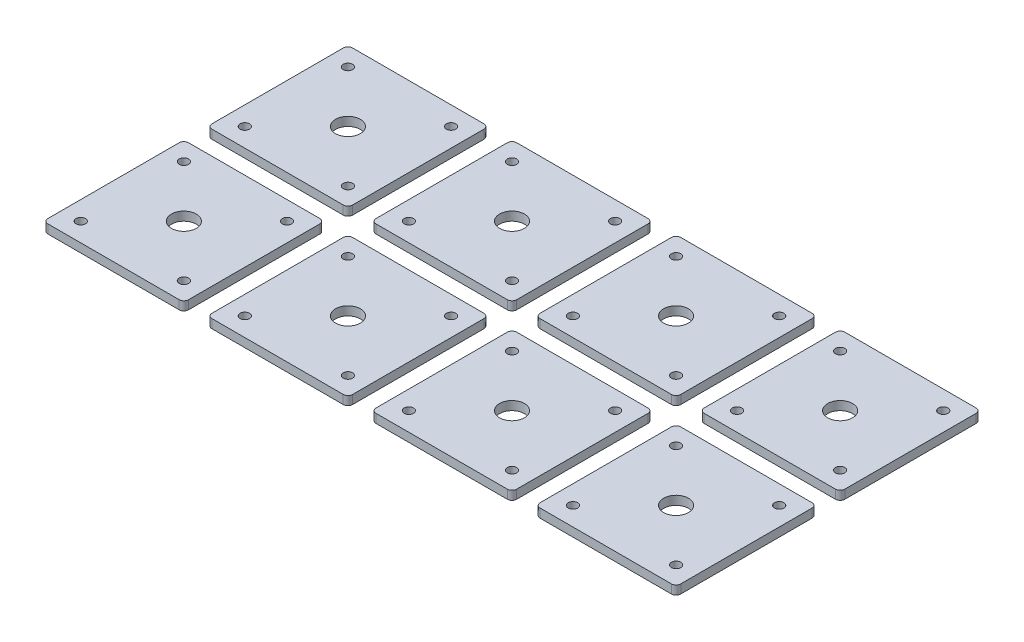
SolidWorks part; units mm, degrees
material "Acrylic (Medium-high impact)"
ref_plane "Front" through (0, 0, 0) normal (0, 0, 1) x (1, 0, 0)
ref_plane "Top" through (0, 0, 0) normal (0, 1, 0) x (1, 0, 0)
ref_plane "Right" through (0, 0, 0) normal (1, 0, 0) x (0, 0, -1)
sketch "Sketch1" plane through (0, 0, 0) normal (0, 0, 1) x (1, 0, 0)
  line L0 (-22.225, 0) -> (22.225, 0)
  dimension "D1" = 44.45
sketch "Sketch2" plane through (0, 0, 0) normal (0, 1, 0) x (1, 0, 0)
  line L0 (-13.97, 13.97) -> (13.97, 13.97) construction
  line L1 (-13.97, 13.97) -> (-13.97, -13.97) construction
  line L2 (-13.97, -13.97) -> (13.97, -13.97) construction
  line L3 (13.97, 13.97) -> (13.97, -13.97) construction
  line L4 (-13.97, 13.97) -> (13.97, -13.97) construction
  line L5 (-13.97, -13.97) -> (13.97, 13.97) construction
  line L7 (-19.05, 19.05) -> (19.05, 19.05)
  line L8 (-19.05, 19.05) -> (-19.05, -19.05)
  line L9 (-19.05, -19.05) -> (19.05, -19.05)
  line L10 (19.05, 19.05) -> (19.05, -19.05)
  line L11 (-19.05, 19.05) -> (19.05, -19.05) construction
  line L12 (-19.05, -19.05) -> (19.05, 19.05) construction
  circle A0 centre (-13.97, 13.97) radius 1.27
  circle A1 centre (-13.97, -13.97) radius 1.27
  circle A2 centre (13.97, -13.97) radius 1.27
  circle A3 centre (13.97, 13.97) radius 1.27
  circle A4 centre (0, 0) radius 3.3655
  point P0 (0, 0)
  point P12 (0, 0)
  dimension "D3" = 2.54
  dimension "D5" = 6.731
  dimension "D1" = 27.94
  dimension "D2" = 27.94
  dimension "D4" = 38.1
extrude "Boss-Extrude1" add sketch "Sketch2" along normal blind 2.3813
fillet "Fillet1" radius 1.27 4 edges at (-19.05, 1.1906, -19.05) (19.05, 1.1906, -19.05) (19.05, 1.1906, 19.05) (-19.05, 1.1906, 19.05)
pattern_linear "LPattern1" count 2 spacing 44.45 along (0, 0, 1) count 4 spacing 44.45 along (1, 0, 0) of bodies 188
